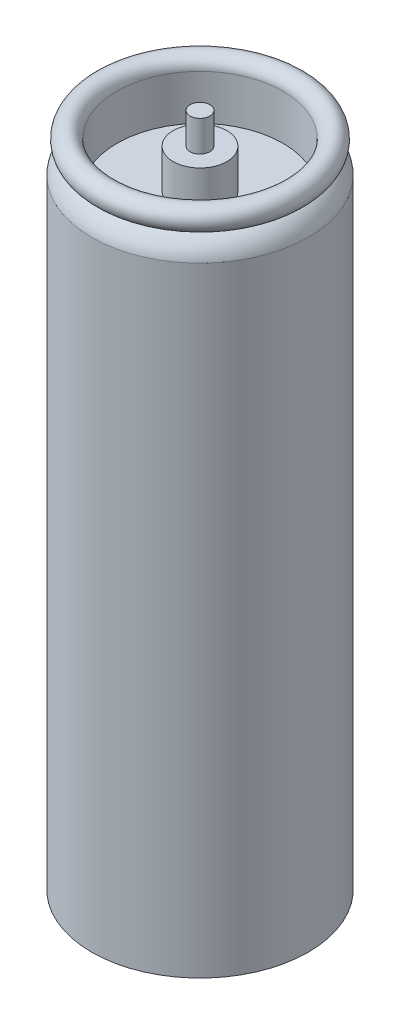
SolidWorks part; units mm, degrees
ref_plane "Front Plane" through (0, 0, 0) normal (0, 0, 1) x (1, 0, 0)
ref_plane "Top Plane" through (0, 0, 0) normal (0, 1, 0) x (1, 0, 0)
ref_plane "Right Plane" through (0, 0, 0) normal (1, 0, 0) x (0, 0, -1)
sketch "Sketch1" plane through (0, 0, 0) normal (0, 0, 1) x (1, 0, 0)
  line L0 (-15.5, 0) -> (-17.5, 0)
  line L1 (-17.5, 0) -> (-17.5, 100)
  line L2 (0, -1000) -> (0, 0) construction
  line L3 (0, 108.9997) -> (-1.5875, 108.9997)
  line L4 (-1.5875, 108.9997) -> (-1.5875, 103.9997)
  line L5 (0, 108.9997) -> (0, 2.7537)
  line L6 (-1.5875, 103.9997) -> (-4.3333, 103.9997)
  line L7 (-4.3333, 103.9997) -> (-4.3333, 97.6924)
  line L8 (-4.3333, 97.6924) -> (-13.4028, 97.6924)
  line L9 (-13.4028, 97.6924) -> (-13.4028, 104.9834)
  line L10 (0, 2.7537) -> (0, 94.3243) construction
  arc A1 (0, 2.7537) -> (-15.5, 0) centre (0, -42.2463) ccw
  arc A3 (-13.4028, 104.9834) -> (-14.6757, 103.2374) centre (-15.2367, 104.9834) ccw
  arc A4 (-14.6757, 103.2374) -> (-17.5, 100) centre (-13.4028, 99.2763) ccw
  point P18 (-13.4028, 99.1169)
  dimension "D4" = 2.7458
  dimension "D7" = 90
  dimension "D9" = 4.1606
  dimension "D10" = 1.8339
  dimension "D1" = 17.5
  dimension "D2" = 100
  dimension "D3" = 1.5875
  dimension "D5" = 5
  dimension "D6" = 2
  dimension "D8" = 9.0696
  dimension "D11" = 6.3074
  dimension "D12" = 108.9997
revolve "Revolve1" add sketch "Sketch1" angle 360 about L2
